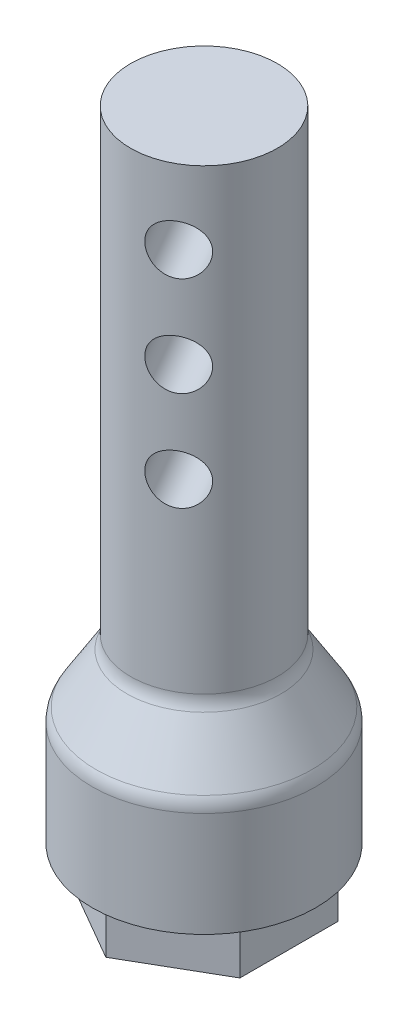
SolidWorks part; units mm, degrees
ref_plane "Piano frontale" through (0, 0, 0) normal (0, 0, 1) x (1, 0, 0)
ref_plane "Piano superiore" through (0, 0, 0) normal (0, 1, 0) x (1, 0, 0)
ref_plane "Piano destro" through (0, 0, 0) normal (1, 0, 0) x (0, 0, -1)
sketch "Schizzo1" plane through (0, 0, 0) normal (0, 0, 1) x (1, 0, 0)
  line L0 (0, 0) -> (4.5, 0)
  line L1 (4.5, 0) -> (4.5, 6.2159)
  line L2 (4.3507, 6.7416) -> (3.1043, 8.7584)
  line L3 (2.955, 9.2841) -> (2.955, 31.7)
  line L4 (2.955, 31.7) -> (0, 31.7)
  line L5 (0, 31.7) -> (0, 0) construction
  line L6 (0, 0) -> (0, 31.7)
  arc A0 (4.5, 6.2159) -> (4.3507, 6.7416) centre (3.5, 6.2159) ccw
  arc A1 (3.1043, 8.7584) -> (2.955, 9.2841) centre (3.955, 9.2841) cw
  point P9 (4.5, 6.5)
  point P12 (2.955, 9)
  dimension "D6" = 1
  dimension "D1" = 31.7
  dimension "D2" = 5.91
  dimension "D3" = 9
  dimension "D4" = 6.5
  dimension "D5" = 2.5
revolve "Rivoluzione1" add sketch "Schizzo1" angle 360 about L5
sketch "Schizzo2" plane through (0, 0, 0) normal (0, -1, 0) x (1, 0, 0)
  line L1 (0, 3.95) -> (-3.4208, 1.975)
  line L2 (-3.4208, 1.975) -> (-3.4208, -1.975)
  line L3 (-3.4208, -1.975) -> (0, -3.95)
  line L4 (0, -3.95) -> (3.4208, -1.975)
  line L5 (3.4208, -1.975) -> (3.4208, 1.975)
  line L6 (3.4208, 1.975) -> (0, 3.95)
  circle A0 centre (0, 0) radius 3.95 construction
  circle A2 centre (0, 0) radius 4.5 construction
  circle A3 centre (0, 0) radius 4.5
  dimension "D1" = 7.9
extrude "Taglio-Estrusione1" cut sketch "Schizzo2" against normal blind 2
hole_wizard "Foro filettato M3x0.5-1" positions "Schizzo4" profile "Schizzo3" tap size "M3x0.5" standard "Ansi Metric"
sketch "Schizzo4" plane through (0, 0, 0) normal (0, -1, 0) x (-1, 0, 0)
  point P0 (0, 0)
sketch "Schizzo3" plane through (0, 0, 0) normal (1, 0, 0) x (0, 0, -1)
  line L0 (0, 0) -> (0, 9.7511)
  line L1 (0, 9.7511) -> (1.25, 9)
  line L2 (1.25, 9) -> (1.25, 0)
  line L5 (1.25, 0) -> (0, 0)
  line L10 (0, 9.7511) -> (-1.25, 9) construction
  line L11 (0, -6.35) -> (0, 107.95) construction
  dimension "Tap Drill Dia." = 2.5
  dimension "Tap Drill Depth" = 9
  dimension "Drill Angle" = 118
cosmetic thread "Filettatura del foro1" parameters "D1"=9, "D2"=3
ref_plane "Piano1" through (-1.4775, 0, -2.5591) normal (-0.5, 0, -0.866) x (-0.866, 0, 0.5)
sketch "Schizzo5" plane through (-1.4775, 0, -2.5591) normal (-0.5, 0, -0.866) x (-0.866, 0, 0.5)
  line L0 (0, 28.7) -> (0, 9.2841) construction
  line L1 (2.955, 9.2841) -> (-2.955, 9.2841) construction
  line L2 (2.955, 31.7) -> (-2.955, 31.7) construction
  circle A0 centre (0, 16.7) radius 1
  circle A1 centre (0, 20.7) radius 1
  circle A2 centre (0, 24.7) radius 1
  circle A3 centre (0, 28.7) radius 1
  dimension "D1" = 2
  dimension "D2" = 12
  dimension "D3" = 4
  dimension "D4" = 4
  dimension "D5" = 3
extrude "Taglio-Estrusione2" cut sketch "Schizzo5" against normal through all
ref_plane "Piano2" through (0, 27.7, 0) normal (0, 1, 0) x (1, 0, 0)
other "TaglioSuperficie1"
